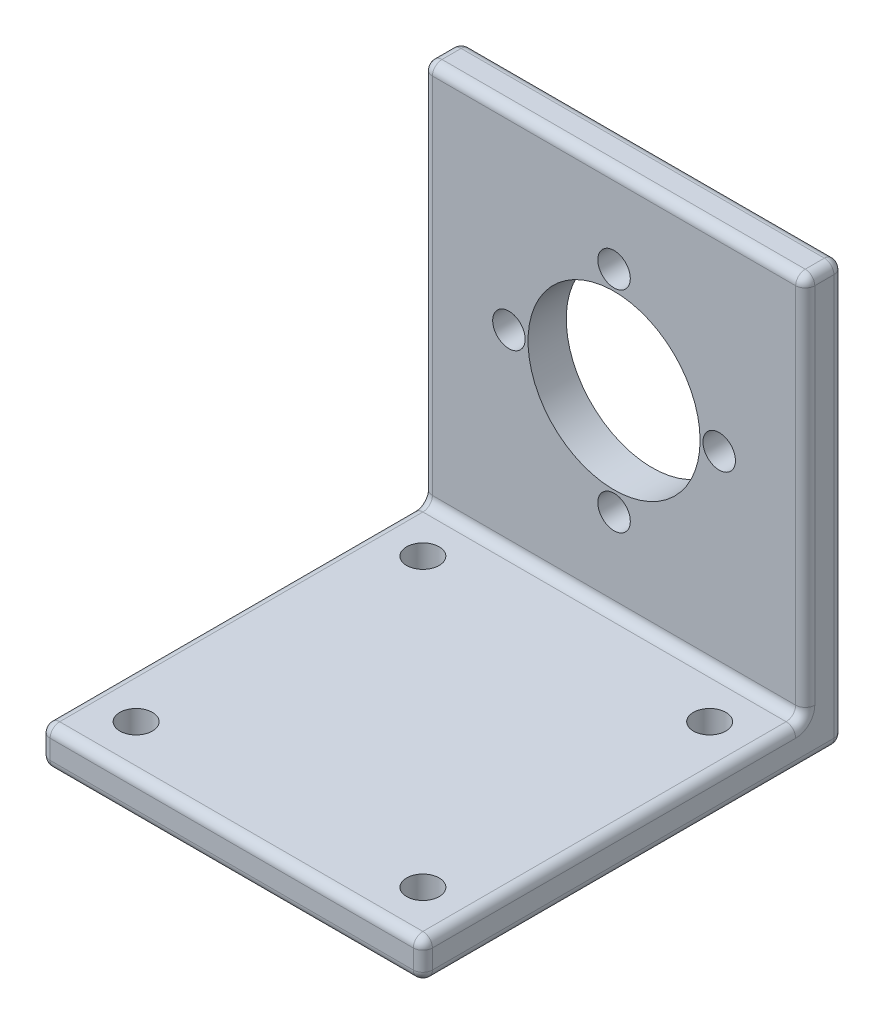
SolidWorks part; units mm, degrees
ref_plane "Front Plane" through (0, 0, 0) normal (0, 0, 1) x (1, 0, 0)
ref_plane "Top Plane" through (0, 0, 0) normal (0, 1, 0) x (1, 0, 0)
ref_plane "Right Plane" through (0, 0, 0) normal (1, 0, 0) x (0, 0, -1)
sketch "Sketch2" plane through (0, 0, 0) normal (0, 0, 1) x (1, 0, 0)
  line L1 (0, 0) -> (40, 0)
  line L2 (0, 0) -> (0, 44)
  line L3 (0, 44) -> (40, 44)
  line L4 (40, 0) -> (40, 44)
  dimension "D1" = 44
  dimension "D2" = 40
extrude "Boss-Extrude1" add sketch "Sketch2" along normal blind 4
sketch "Sketch4" plane through (0, 0, 4) normal (0, 0, 1) x (1, 0, 0)
  line L0 (40, 0) -> (40, 44) construction
  line L1 (0, 0) -> (40, 0)
  line L2 (0, 0) -> (0, 4)
  line L3 (0, 4) -> (40, 4)
  line L4 (40, 0) -> (40, 4)
  dimension "D1" = 4
  dimension "D2" = 40
extrude "Boss-Extrude2" add sketch "Sketch4" along normal blind 40
sketch "Sketch5" plane through (0, 0, 4) normal (0, 0, 1) x (1, 0, 0)
  line L0 (20, 44) -> (20, 4)
  line L1 (40, 44) -> (0, 44) construction
  line L2 (40, 4) -> (0, 4) construction
  circle A0 centre (20, 24) radius 9
  circle A2 centre (20, 35) radius 1.7
  circle A3 centre (9, 24) radius 1.7
  circle A4 centre (20, 13) radius 1.7
  circle A5 centre (31, 24) radius 1.7
  dimension "D1" = 18
  dimension "D3" = 3.4
  dimension "D4" = 3.4
  dimension "D5" = 3.4
  dimension "D6" = 3.4
extrude "Cut-Extrude1" cut sketch "Sketch5" against normal through all contours L0 A0 | L0 A0 | A3 | A2 | A5 | A4
sketch "Sketch8" plane through (0, 4, 0) normal (0, 1, 0) x (1, 0, 0)
  line L0 (40, -4) -> (0, -4) construction
  line L1 (0, -44) -> (0, -4) construction
  line L2 (40, -44) -> (40, -4) construction
  line L3 (40, -44) -> (0, -44) construction
  circle A0 centre (5, -9) radius 1.7
  circle A1 centre (35, -9) radius 1.7
  circle A2 centre (35, -39) radius 1.7
  circle A3 centre (5, -39) radius 1.7
  dimension "D1" = 5
  dimension "D11" = 3.4
  dimension "D12" = 3.4
  dimension "D13" = 3.4
  dimension "D14" = 3.4
  dimension "D2" = 5
  dimension "D3" = 5
  dimension "D4" = 5
  dimension "D5" = 5
  dimension "D6" = 5
  dimension "D7" = 5
  dimension "D8" = 5
  dimension "D9" = 5
  dimension "D10" = 5
extrude "Cut-Extrude4" cut sketch "Sketch8" against normal through all
fillet "Fillet2" radius 1 18 edges at (20, 4, 44) (20, 0, 44) (0, 24, 4) (0, 4, 24) (0, 2, 44) (0, 0, 22) (0, 22, 0) (20, 44, 4) (0, 44, 2) (20, 44, 0) (40, 0, 22) (40, 2, 44) (40, 4, 24) (40, 24, 4) (40, 44, 2) (40, 22, 0) (20, 0, 0) (20, 4, 4)
